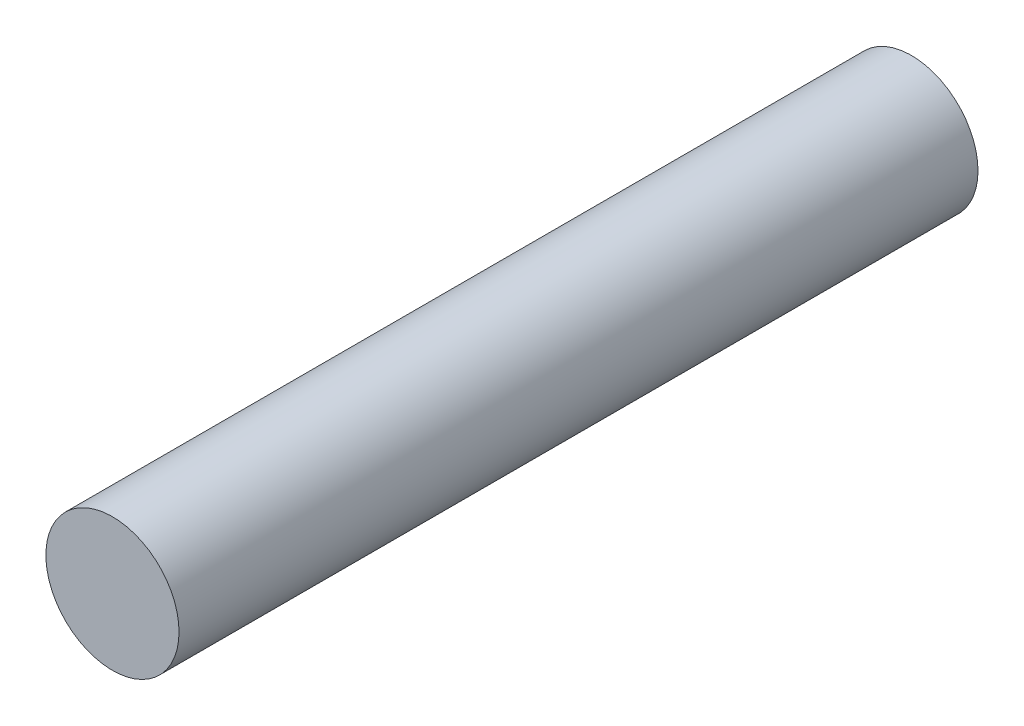
SolidWorks part; units mm, degrees
ref_plane "Спереди" through (0, 0, 0) normal (0, 0, 1) x (1, 0, 0)
ref_plane "Сверху" through (0, 0, 0) normal (0, 1, 0) x (1, 0, 0)
ref_plane "Справа" through (0, 0, 0) normal (1, 0, 0) x (0, 0, -1)
sketch "Эскиз1" plane through (0, 0, 0) normal (0, 0, 1) x (1, 0, 0)
  circle A0 centre (0, 0) radius 12.5
extrude "Бобышка-Вытянуть1" add sketch "Эскиз1" along normal blind 150
